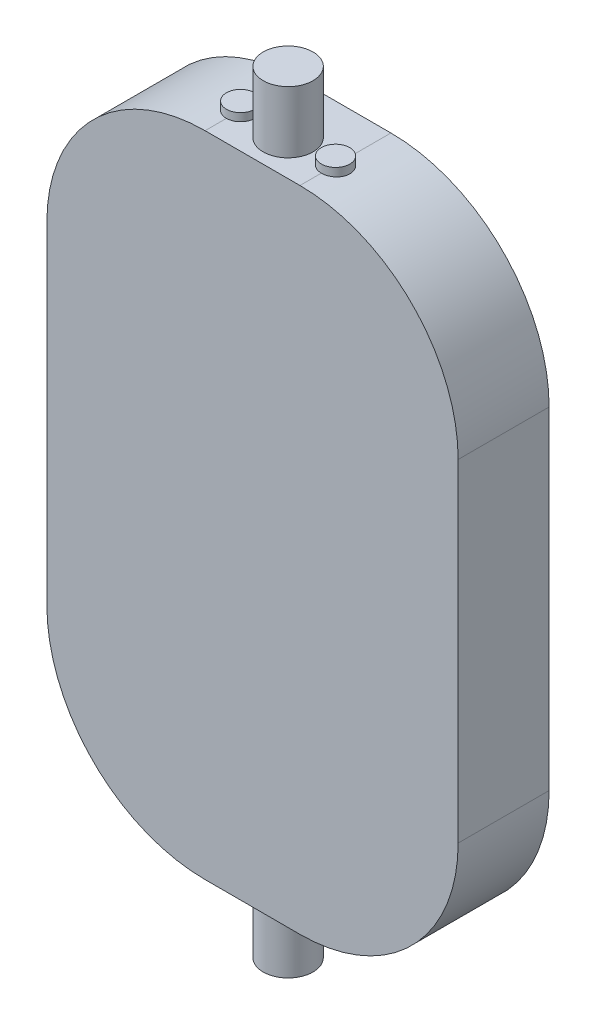
SolidWorks part; units mm, degrees
ref_plane "Front Plane" through (0, 0, 0) normal (0, 0, 1) x (1, 0, 0)
ref_plane "Top Plane" through (0, 0, 0) normal (0, 1, 0) x (1, 0, 0)
ref_plane "Right Plane" through (0, 0, 0) normal (1, 0, 0) x (0, 0, -1)
sketch "Sketch1" plane through (0, 0, 0) normal (0, 0, 1) x (1, 0, 0)
  line L0 (-26, 21) -> (-26, -21)
  line L1 (-26, -41) -> (26, -41) construction
  line L2 (-26, -41) -> (-26, 41) construction
  line L3 (-26, 41) -> (26, 41) construction
  line L4 (26, -41) -> (26, 41) construction
  line L5 (0, 41) -> (0, -41) construction
  line L6 (-26, 0) -> (26, 0) construction
  line L7 (26, 21) -> (26, -21)
  line L8 (-6, 41) -> (6, 41)
  line L9 (-6, -41) -> (6, -41)
  arc A0 (-6, 41) -> (-26, 21) centre (-6, 21) ccw
  arc A1 (6, 41) -> (26, 21) centre (6, 21) cw
  arc A2 (6, -41) -> (26, -21) centre (6, -21) ccw
  arc A3 (-6, -41) -> (-26, -21) centre (-6, -21) cw
  point P0 (0, 0)
  dimension "D3" = 20
  dimension "D1" = 82
  dimension "D2" = 52
extrude "Boss-Extrude1" add sketch "Sketch1" along normal blind 11.5
sketch "Sketch2" plane through (0, 41, 0) normal (0, 1, 0) x (1, 0, 0)
  line L0 (6, -11.5) -> (-6, -11.5) construction
  circle A0 centre (0, -7) radius 3.15
  point P5 (0, 0)
  point P6 (0, 0)
  dimension "D1" = 6.3
  dimension "D2" = 4.5
extrude "Boss-Extrude2" add sketch "Sketch2" along normal blind 7.8
sketch "Sketch3" plane through (0, 41, 0) normal (0, 1, 0) x (1, 0, 0)
  line L0 (-6, -7) -> (6, -7) construction
  circle A0 centre (-6, -7) radius 1.8
  circle A1 centre (6, -7) radius 1.8
  point P4 (0, -7)
  dimension "D1" = 3.6
  dimension "D2" = 12
extrude "Boss-Extrude3" add sketch "Sketch3" along normal blind 1 and the other way blind 1
mirror "Mirror1" about plane through (0, 0, 0) normal (0, 1, 0) of "Boss-Extrude3", "Boss-Extrude2"
